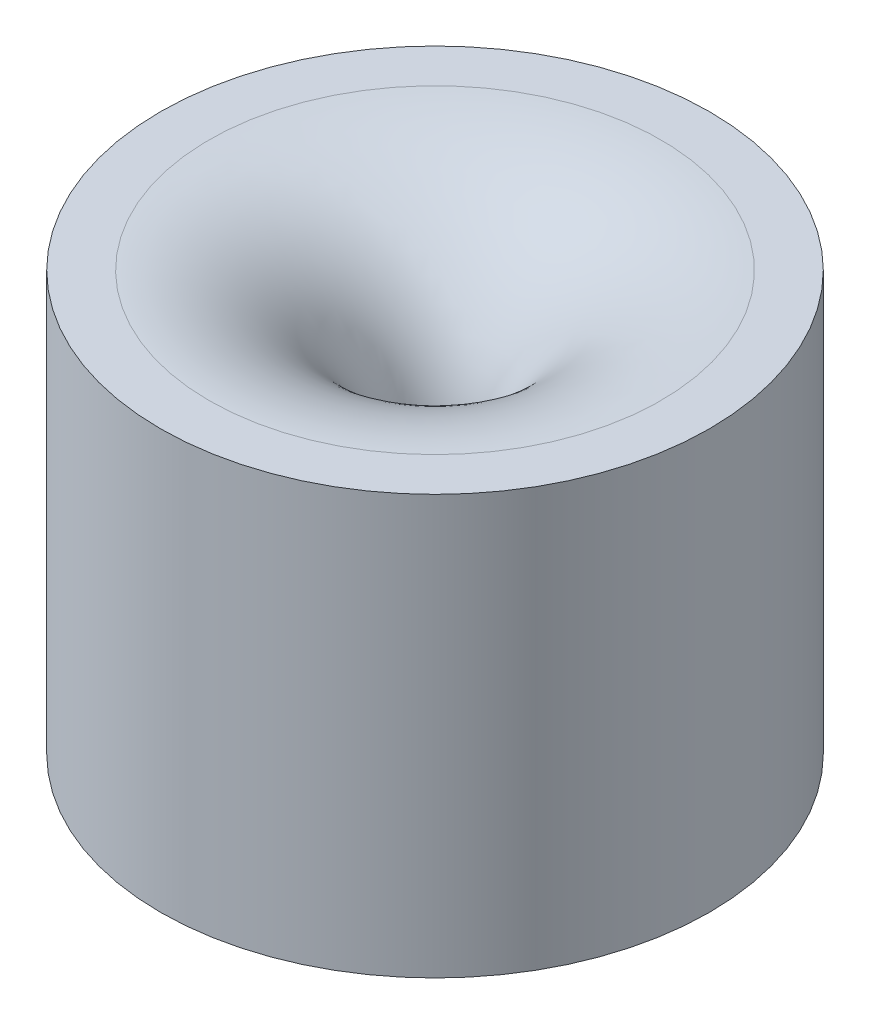
SolidWorks part; units mm, degrees
ref_plane "Front Plane" through (0, 0, 0) normal (0, 0, 1) x (1, 0, 0)
ref_plane "Top Plane" through (0, 0, 0) normal (0, 1, 0) x (1, 0, 0)
ref_plane "Right Plane" through (0, 0, 0) normal (1, 0, 0) x (0, 0, -1)
sketch "Sketch1" plane through (0, 0, 0) normal (0, 1, 0) x (1, 0, 0)
  circle A0 centre (0, 0) radius 4
  circle A1 centre (0, 0) radius 29.175
  dimension "D1" = 8
  dimension "D2" = 58.35
extrude "Boss-Extrude1" add sketch "Sketch1" along normal blind 44.5
fillet "Fillet1" radius 20 1 edges at (0, 44.5, 4)
sketch "Sketch2" plane through (0, 0, 0) normal (0, -1, 0) x (1, 0, 0)
  circle A0 centre (0, 0) radius 11
  dimension "D1" = 22
extrude "Cut-Extrude1" cut sketch "Sketch2" against normal blind 10
